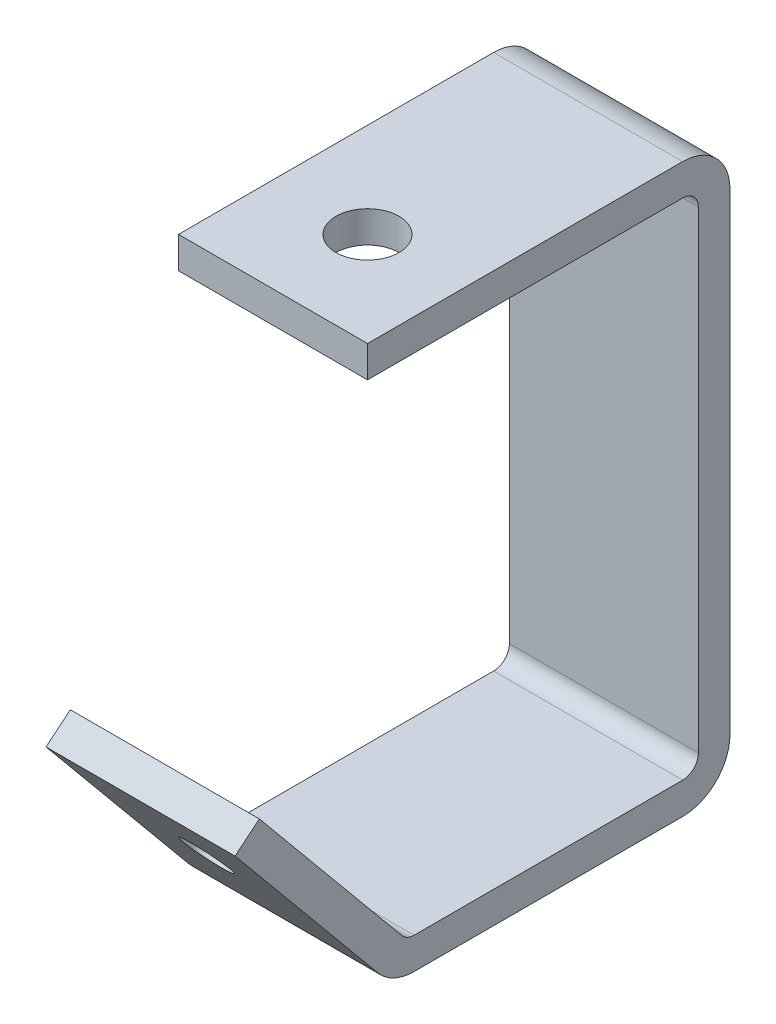
SolidWorks part; units mm, degrees
ref_plane "Ön Düzlem" through (0, 0, 0) normal (0, 0, 1) x (1, 0, 0)
ref_plane "Üst Düzlem" through (0, 0, 0) normal (0, 1, 0) x (1, 0, 0)
ref_plane "Sağ Düzlem" through (0, 0, 0) normal (1, 0, 0) x (0, 0, -1)
sketch "Çizim1" plane through (0, 0, 0) normal (1, 0, 0) x (0, 0, -1)
  line L0 (0, 0) -> (63.51, 0)
  line L1 (73.04, -9.53) -> (73.04, -104.78)
  line L2 (63.51, -114.31) -> (9.39, -114.31)
  line L3 (2.047, -110.8547) -> (-26.6945, -76.1122)
  line L4 (0, -6.35) -> (63.51, -6.35)
  line L5 (66.69, -9.53) -> (66.69, -104.78)
  line L6 (63.51, -107.96) -> (9.39, -107.96)
  line L7 (6.9398, -106.807) -> (-21.8017, -72.0646)
  line L8 (-26.6945, -76.1122) -> (-21.8017, -72.0646)
  line L9 (0, 0) -> (0, -6.35)
  arc A0 (63.51, 0) -> (73.04, -9.53) centre (63.51, -9.53) cw
  arc A1 (73.04, -104.78) -> (63.51, -114.31) centre (63.51, -104.78) cw
  arc A2 (9.39, -114.31) -> (2.047, -110.8547) centre (9.39, -104.78) cw
  arc A3 (63.51, -6.35) -> (66.69, -9.53) centre (63.51, -9.53) cw
  arc A4 (66.69, -104.78) -> (63.51, -107.96) centre (63.51, -104.78) cw
  arc A5 (9.39, -107.96) -> (6.9398, -106.807) centre (9.39, -104.78) cw
  dimension "D1" = 63.51
  dimension "D5" = 9.53
  dimension "D6" = 9.53
  dimension "D7" = 9.53
  dimension "D2" = 95.25
  dimension "D3" = 54.12
  dimension "D4" = 45.09
  dimension "D8" = 6.35
extrude "Yükseklik-Ekstrüzyon1" add sketch "Çizim1" along normal blind 38.1
sketch "Çizim2" plane through (0, 0, 0) normal (0, 1, 0) x (1, 0, 0)
  line L0 (0, 63.51) -> (0, 0) construction
  line L1 (38.1, 0) -> (0, 0) construction
  circle A0 centre (19.05, 19.04) radius 6.35
  dimension "D1" = 12.7
  dimension "D2" = 19.05
  dimension "D3" = 19.04
extrude "Kes-Ekstrüzyon1" cut sketch "Çizim2" against normal up to next
sketch "Çizim3" plane through (0, -44.036, 53.2303) normal (0, -0.6374, 0.7705) x (1, 0, 0)
  line L0 (38.1, -41.6298) -> (38.1, -86.7198) construction
  line L1 (38.1, -41.6298) -> (0, -41.6298) construction
  circle A0 centre (19.05, -62.4398) radius 4.765
  point P4 (0, 0)
  dimension "D1" = 9.53
  dimension "D2" = 19.05
  dimension "D3" = 20.81
extrude "Kes-Ekstrüzyon2" cut sketch "Çizim3" against normal up to next
